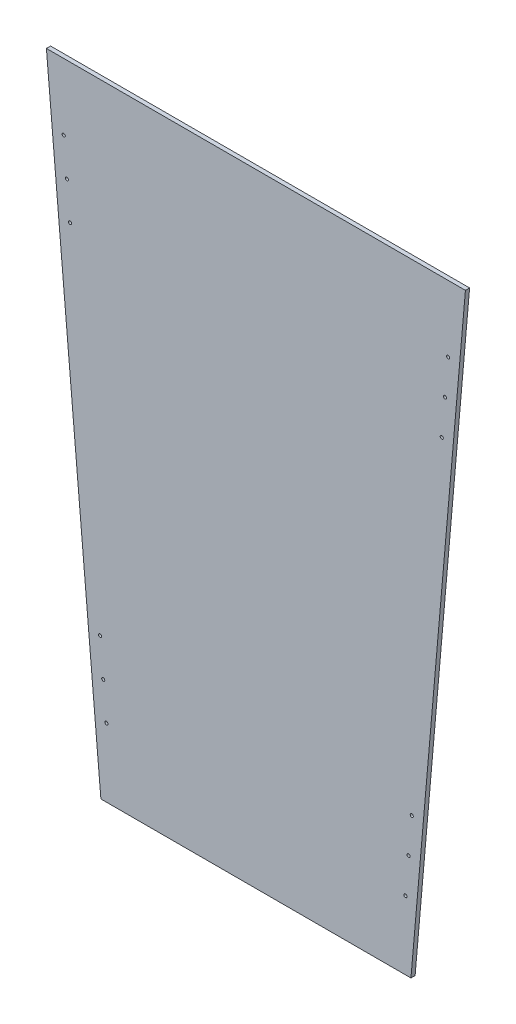
SolidWorks part; units mm, degrees
material "Oak"
ref_plane "Front Plane" through (0, 0, 0) normal (0, 0, 1) x (1, 0, 0)
ref_plane "Top Plane" through (0, 0, 0) normal (0, 1, 0) x (1, 0, 0)
ref_plane "Right Plane" through (0, 0, 0) normal (1, 0, 0) x (0, 0, -1)
sketch "Sketch2" plane through (0, 0, 0) normal (0, 0, 1) x (1, 0, 0)
  line L0 (-201.085, 510.5193) -> (-148.79, -87.2007)
  line L1 (-201.085, 510.5193) -> (201.085, 510.5193)
  line L3 (-148.79, -87.2007) -> (148.79, -87.2007)
  line L5 (201.085, 510.5193) -> (148.79, -87.2007)
  line L6 (0, 0) -> (0, 174.9611) construction
  circle A0 centre (-143.497, -21.4907) radius 1.5
  circle A1 centre (-146.5475, 13.3761) radius 1.5
  circle A2 centre (-149.5979, 48.2429) radius 1.5
  circle A3 centre (-178.3603, 376.9893) radius 1.5
  circle A4 centre (-181.4108, 411.8561) radius 1.5
  circle A5 centre (-184.4612, 446.7229) radius 1.5
  circle A6 centre (143.497, -21.4907) radius 1.5
  circle A7 centre (146.5475, 13.3761) radius 1.5
  circle A8 centre (149.5979, 48.2429) radius 1.5
  circle A9 centre (178.3603, 376.9893) radius 1.5
  circle A10 centre (181.4108, 411.8561) radius 1.5
  circle A11 centre (184.4612, 446.7229) radius 1.5
  point P0 (0, 0)
  point P6 (0, 510.5193)
  point P7 (0, -87.2007)
  dimension "D4" = 65.71
  dimension "D6" = 3
  dimension "D8" = 3
  dimension "D1" = 297.58
  dimension "D2" = 402.17
  dimension "D3" = 597.72
  dimension "D5" = 11
  dimension "D9" = 464.19
  dimension "D10" = 11
  dimension "D7" = 3
  dimension "D11" = 3
extrude "Boss-Extrude1" add sketch "Sketch2" along normal blind 4
